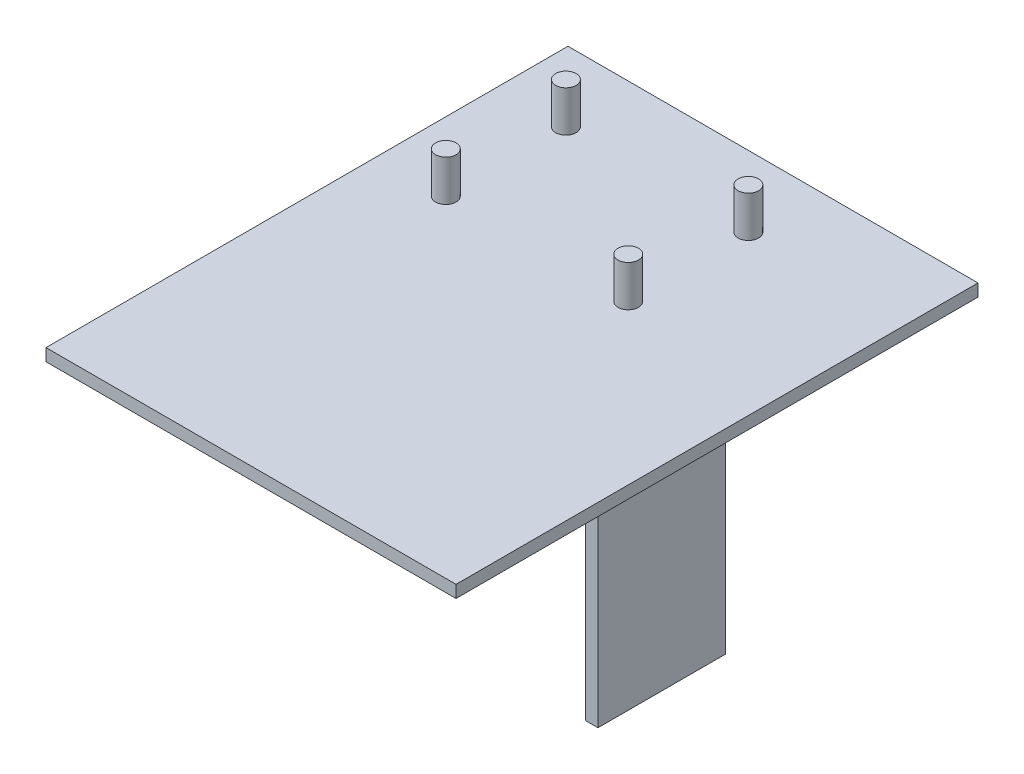
SolidWorks part; units mm, degrees
ref_plane "Alzado" through (0, 0, 0) normal (0, 0, 1) x (1, 0, 0)
ref_plane "Planta" through (0, 0, 0) normal (0, 1, 0) x (1, 0, 0)
ref_plane "Vista lateral" through (0, 0, 0) normal (1, 0, 0) x (0, 0, -1)
sketch "Croquis1" plane through (0, 0, 0) normal (0, 1, 0) x (1, 0, 0)
  line L1 (-50, 63.6524) -> (50, 63.6524)
  line L2 (-50, 63.6524) -> (-50, -63.6524)
  line L3 (-50, -63.6524) -> (50, -63.6524)
  line L4 (50, 63.6524) -> (50, -63.6524)
  line L5 (-50, 63.6524) -> (50, -63.6524) construction
  line L6 (-50, -63.6524) -> (50, 63.6524) construction
  point P0 (0, 0)
  dimension "D1" = 100
extrude "Saliente-Extruir1" add sketch "Croquis1" along normal blind 3
sketch "Croquis2" plane through (0, 0, 0) normal (0, -1, 0) x (1, 0, 0)
  line L1 (34.6108, 13.6473) -> (31.6108, 13.6473)
  line L2 (34.6108, 13.6473) -> (34.6108, -17.4962)
  line L3 (34.6108, -17.4962) -> (31.6108, -17.4962)
  line L4 (31.6108, 13.6473) -> (31.6108, -17.4962)
  dimension "D1" = 3
extrude "Saliente-Extruir2" add sketch "Croquis2" along normal blind 60
sketch "Croquis3" plane through (0, 3, 0) normal (0, 1, 0) x (1, 0, 0)
  line L1 (11.2613, 46.3787) -> (-33.2337, 46.3787) construction
  line L2 (11.2613, 46.3787) -> (11.2613, 17.0874) construction
  line L3 (11.2613, 17.0874) -> (-33.2337, 17.0874) construction
  line L4 (-33.2337, 46.3787) -> (-33.2337, 17.0874) construction
  circle A0 centre (11.2613, 46.3787) radius 2.5
  circle A1 centre (11.2613, 17.0874) radius 2.5
  circle A2 centre (-33.2337, 17.0874) radius 2.5
  circle A3 centre (-33.2337, 46.3787) radius 2.5
  dimension "D1" = 5
extrude "Saliente-Extruir3" add sketch "Croquis3" along normal blind 10
